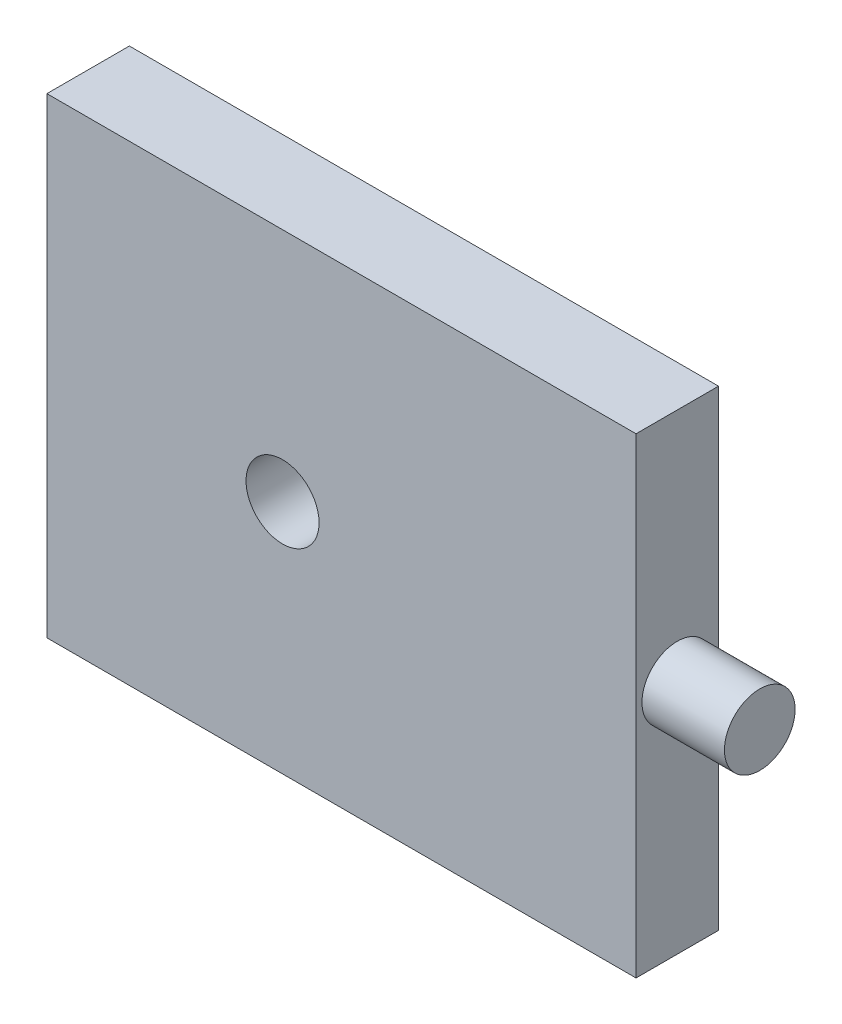
SolidWorks part; units mm, degrees
ref_plane "前视基准面" through (0, 0, 0) normal (0, 0, 1) x (1, 0, 0)
ref_plane "上视基准面" through (0, 0, 0) normal (0, 1, 0) x (1, 0, 0)
ref_plane "右视基准面" through (0, 0, 0) normal (1, 0, 0) x (0, 0, -1)
sketch "草图1" plane through (0, 0, 0) normal (0, 0, 1) x (1, 0, 0)
  line L0 (12.5, 0) -> (-2.5, 0) construction
  line L1 (12.5, -10) -> (-12.5, -10)
  line L2 (12.5, -10) -> (12.5, 10)
  line L3 (12.5, 10) -> (-12.5, 10)
  line L4 (-12.5, -10) -> (-12.5, 10)
  line L5 (12.5, -10) -> (-12.5, 10) construction
  line L6 (12.5, 10) -> (-12.5, -10) construction
  circle A0 centre (-2.5, 0) radius 1.55
  point P0 (0, 0)
  dimension "D4" = 3.1
  dimension "D1" = 25
  dimension "D2" = 20
  dimension "D3" = 15
extrude "凸台-拉伸1" add sketch "草图1" along normal blind 3.5
sketch "草图2" plane through (12.5, 0, 0) normal (1, 0, 0) x (0, 0, -1)
  line L0 (-3.5, 0) -> (0, 0) construction
  line L1 (-3.5, -10) -> (-3.5, 10) construction
  line L2 (0, -10) -> (0, 10) construction
  circle A0 centre (-1.75, 0) radius 1.5
  dimension "D1" = 3
extrude "凸台-拉伸2" add sketch "草图2" along normal blind 3.5
